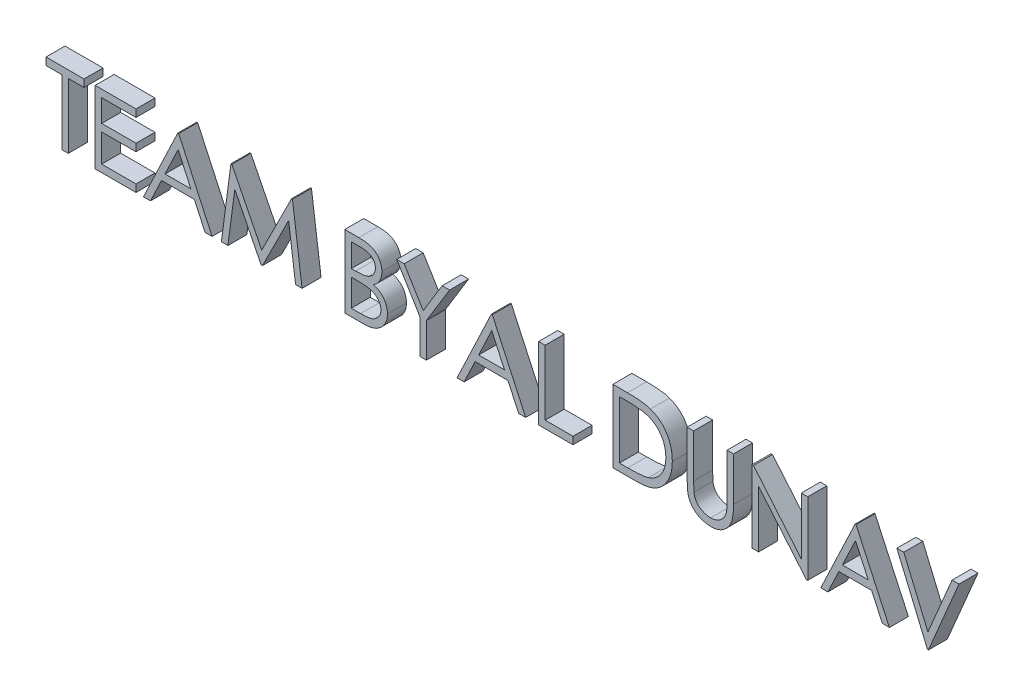
SolidWorks part; units mm, degrees
ref_plane "Front Plane" through (0, 0, 0) normal (0, 0, 1) x (1, 0, 0)
ref_plane "Top Plane" through (0, 0, 0) normal (0, 1, 0) x (1, 0, 0)
ref_plane "Right Plane" through (0, 0, 0) normal (1, 0, 0) x (0, 0, -1)
sketch "Sketch1" plane through (0, 0, 0) normal (0, 0, 1) x (1, 0, 0)
  line L0 (-107.8135, 0) -> (118.784, 0) construction
  text T0 "TEAM BYAL DUNAV" font "Century Gothic" height in points 72
extrude "Boss-Extrude1" add sketch "Sketch1" along normal blind 5
